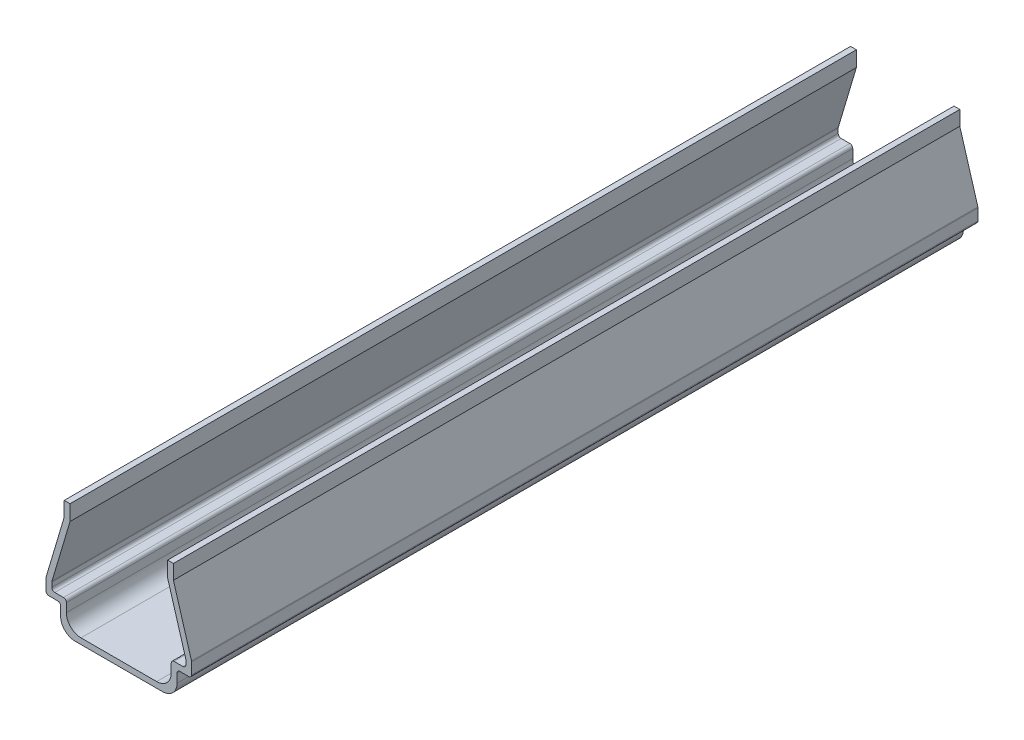
SolidWorks part; units mm, degrees
ref_plane "Front Plane" through (0, 0, 0) normal (0, 0, 1) x (1, 0, 0)
ref_plane "Top Plane" through (0, 0, 0) normal (0, 1, 0) x (1, 0, 0)
ref_plane "Right Plane" through (0, 0, 0) normal (1, 0, 0) x (0, 0, -1)
sketch "Sketch1" plane through (0, 0, 0) normal (0, 0, 1) x (1, 0, 0)
  line L0 (0, 0) -> (0, 7.1478) construction
  line L1 (4, 0) -> (-4, 0)
  line L2 (-4, 0) -> (-4, 1.8)
  line L3 (-4, 1.8) -> (-5, 1.8)
  line L4 (-5, 1.8) -> (-5, 2.8)
  line L5 (4, 0) -> (4, 1.8)
  line L6 (4, 1.8) -> (5, 1.8)
  line L7 (5, 1.8) -> (5, 2.8)
  line L8 (-5, 2.8) -> (-3.75, 7)
  line L9 (-3.75, 7) -> (-3.75, 8)
  line L10 (3.75, 7) -> (3.75, 8)
  line L11 (5, 2.8) -> (3.75, 7)
  dimension "D1" = 8
  dimension "D2" = 10
  dimension "D3" = 1.8
  dimension "D4" = 8
  dimension "D5" = 1
  dimension "D6" = 1
  dimension "D7" = 7.5
extrude "Extrude-Thin1" add sketch "Sketch1" along normal blind 54 thin
fillet "Fillet1" radius 1 4 edges at (3.6, 0.4, 27) (4, 0, 27) (-4, 0, 27) (-3.6, 0.4, 27)
fillet "Fillet2" radius 0.2 12 edges at (5, 2.8, 27) (4.6, 2.2, 27) (-4.6, 2.7417, 27) (-5, 2.8, 27) (-4.6, 2.2, 27) (5, 1.8, 27) (-5, 1.8, 27) (4.6, 2.7417, 27) (4, 1.8, 27) (3.6, 2.2, 27) (-4, 1.8, 27) (-3.6, 2.2, 27)
